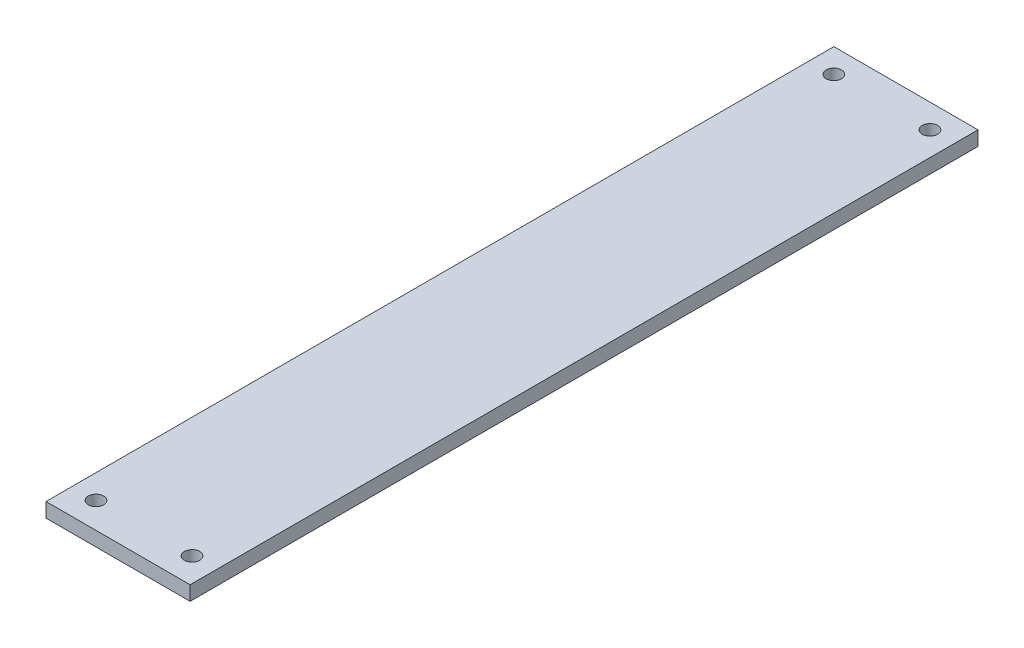
SolidWorks part; units mm, degrees
ref_plane "Front Plane" through (0, 0, 0) normal (0, 0, 1) x (1, 0, 0)
ref_plane "Top Plane" through (0, 0, 0) normal (0, 1, 0) x (1, 0, 0)
ref_plane "Right Plane" through (0, 0, 0) normal (1, 0, 0) x (0, 0, -1)
sketch "Sketch1" plane through (0, 0, 0) normal (0, 1, 0) x (1, 0, 0)
  line L1 (0, 0) -> (30, 0)
  line L2 (0, 0) -> (0, 164)
  line L3 (0, 164) -> (30, 164)
  line L4 (30, 0) -> (30, 164)
  dimension "D1" = 30
  dimension "D2" = 164
extrude "Boss-Extrude1" add sketch "Sketch1" along normal blind 3
sketch "Sketch2" plane through (0, 3, 0) normal (0, 1, 0) x (1, 0, 0)
  line L0 (30, 164) -> (0, 164) construction
  line L1 (30, 0) -> (30, 164) construction
  circle A0 centre (25, 159) radius 1.6
  circle A1 centre (25, 5.4) radius 1.6
  circle A2 centre (5, 159) radius 1.6
  circle A3 centre (5, 5.4) radius 1.6
  dimension "D1" = 3.2
  dimension "D4" = 3.2
  dimension "D2" = 5
  dimension "D3" = 5
  dimension "D5" = 153.6
  dimension "D6" = 5
  dimension "D7" = 20
  dimension "D8" = 20
extrude "Cut-Extrude1" cut sketch "Sketch2" against normal blind 10
